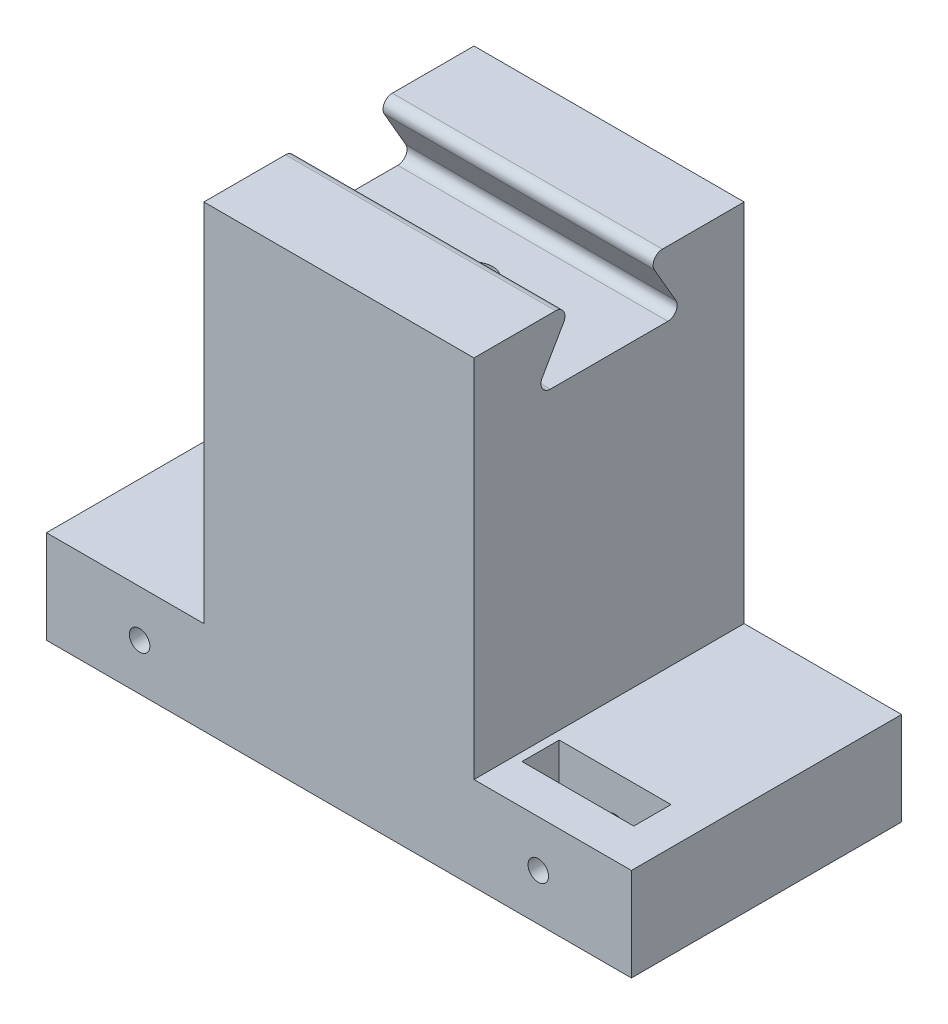
SolidWorks part; units mm, degrees
ref_plane "Front Plane" through (0, 0, 0) normal (0, 0, 1) x (1, 0, 0)
ref_plane "Top Plane" through (0, 0, 0) normal (0, 1, 0) x (1, 0, 0)
ref_plane "Right Plane" through (0, 0, 0) normal (1, 0, 0) x (0, 0, -1)
sketch "Sketch1" plane through (0, 0, 0) normal (0, 1, 0) x (1, 0, 0)
  line L1 (-7.25, -7.25) -> (7.25, -7.25)
  line L2 (-7.25, -7.25) -> (-7.25, 7.25)
  line L3 (-7.25, 7.25) -> (7.25, 7.25)
  line L4 (7.25, -7.25) -> (7.25, 7.25)
  line L5 (-7.25, -7.25) -> (7.25, 7.25) construction
  line L6 (-7.25, 7.25) -> (7.25, -7.25) construction
  point P0 (0, 0)
  dimension "D1" = 14.5
extrude "Boss-Extrude1" add sketch "Sketch1" along normal blind 24.6
sketch "Sketch2" plane through (0, 0, 0) normal (1, 0, 0) x (0, 0, -1)
  line L0 (-2, 24.6) -> (2, 24.6)
  line L1 (-7.25, 24.6) -> (7.25, 24.6) construction
  line L2 (2, 24.6) -> (4.0207, 21.1)
  line L3 (4.0207, 21.1) -> (-4.0207, 21.1)
  line L4 (0, 21.1) -> (0, 24.6) construction
  line L5 (-2, 24.6) -> (-4.0207, 21.1)
  dimension "D1" = 2
  dimension "D2" = 60
  dimension "D3" = 3.5
extrude "Cut-Extrude1" cut sketch "Sketch2" against normal mid plane 20
sketch "Sketch4" plane through (0, 0, 0) normal (0, -1, 0) x (1, 0, 0)
  circle A0 centre (0, 0) radius 4
  dimension "D1" = 8
extrude "Boss-Extrude2" add sketch "Sketch4" along normal blind 2
sketch "Sketch3" plane through (0, 0, 0) normal (1, 0, 0) x (0, 0, -1)
  line L0 (-7.25, 0) -> (7.25, 0) construction
  line L1 (3.302, 0) -> (3.302, -3.302)
  line L2 (3.302, -3.302) -> (0, -3.302)
  line L3 (0, 0) -> (0, -3.302)
  line L4 (0, 0) -> (0, 3.302)
  arc A0 (3.302, 0) -> (0, 3.302) centre (0, 0) ccw
  dimension "D1" = 6.604
revolve "Cut-Revolve1" cut sketch "Sketch3" angle 360 about L4
fillet "Fillet1" radius 0.5 4 edges at (0, 21.1, -4.0207) (0, 21.1, 4.0207) (0, 24.6, 2) (0, 24.6, -2)
sketch "Sketch6" plane through (0, 0, 0) normal (0, 1, 0) x (1, 0, 0)
  line L1 (-7.25, -7.25) -> (7.25, -7.25)
  line L2 (-7.25, -7.25) -> (-7.25, 7.25)
  line L3 (-7.25, 7.25) -> (7.25, 7.25)
  line L4 (7.25, -7.25) -> (7.25, 7.25)
  line L5 (-7.25, -7.25) -> (7.25, 7.25) construction
  line L6 (-7.25, 7.25) -> (7.25, -7.25) construction
  line L7 (-15.7, -7.25) -> (15.7, -7.25)
  line L8 (-15.7, -7.25) -> (-15.7, 7.25)
  line L9 (-15.7, 7.25) -> (15.7, 7.25)
  line L10 (15.7, -7.25) -> (15.7, 7.25)
  line L11 (-15.7, -7.25) -> (15.7, 7.25) construction
  line L12 (-15.7, 7.25) -> (15.7, -7.25) construction
  point P0 (0, 0)
  point P7 (0, 0)
  dimension "D1" = 31.4
extrude "Boss-Extrude3" add sketch "Sketch6" along normal blind 5 contours L7 L10 L9 L4 | L9 L8 L7 L2
sketch "Sketch7" plane through (0, 0, 0) normal (0, -1, 0) x (1, 0, 0)
  line L0 (-15.7, 7.25) -> (-15.7, -7.25) construction
  line L1 (13.7, 3.125) -> (7.7, 3.125)
  line L2 (13.7, 3.125) -> (13.7, 5.125)
  line L3 (13.7, 5.125) -> (7.7, 5.125)
  line L4 (7.7, 3.125) -> (7.7, 5.125)
  line L5 (13.7, 3.125) -> (7.7, 5.125) construction
  line L6 (13.7, 5.125) -> (7.7, 3.125) construction
  line L7 (-7.7, -5.125) -> (-13.7, -5.125)
  line L8 (-7.7, -5.125) -> (-7.7, -3.125)
  line L9 (-7.7, -3.125) -> (-13.7, -3.125)
  line L10 (-13.7, -5.125) -> (-13.7, -3.125)
  line L11 (-7.7, -5.125) -> (-13.7, -3.125) construction
  line L12 (-7.7, -3.125) -> (-13.7, -5.125) construction
  line L13 (-13.7, -5.125) -> (-13.7, -7.25) construction
  line L14 (15.7, -7.25) -> (-15.7, -7.25) construction
  line L15 (15.7, 7.25) -> (15.7, -7.25) construction
  line L16 (13.7, 5.125) -> (13.7, 7.25) construction
  line L18 (-15.7, 7.25) -> (15.7, 7.25) construction
  point P0 (10.7, 4.125)
  point P5 (-10.7, -4.125)
  dimension "D1" = 2
  dimension "D2" = 2
  dimension "D3" = 10.25
  dimension "D5" = 2
  dimension "D6" = 6
extrude "Cut-Extrude2" cut sketch "Sketch7" against normal blind 5
sketch "Sketch8" plane through (0, 0, -7.25) normal (0, 0, -1) x (-1, 0, 0)
  line L0 (-13.7, 5) -> (-13.7, 0) construction
  line L1 (13.7, 5) -> (13.7, 0) construction
  line L2 (-15.7, 0) -> (15.7, 0) construction
  circle A0 centre (-10.7, 2.5) radius 0.55
  circle A1 centre (10.7, 2.5) radius 0.55
  point P6 (-13.7, 2.5)
  dimension "D5" = 1.1
  dimension "D6" = 1.1
  dimension "D1" = 3
  dimension "D2" = 3
  dimension "D3" = 2.5
  dimension "D4" = 2.5
extrude "Cut-Extrude3" cut sketch "Sketch8" against normal through all
sketch "Sketch9" plane through (0, 21.1, 0) normal (0, 1, 0) x (1, 0, 0)
  circle A0 centre (0, 0) radius 1
  dimension "D1" = 2
extrude "Cut-Extrude4" cut sketch "Sketch9" against normal through all
